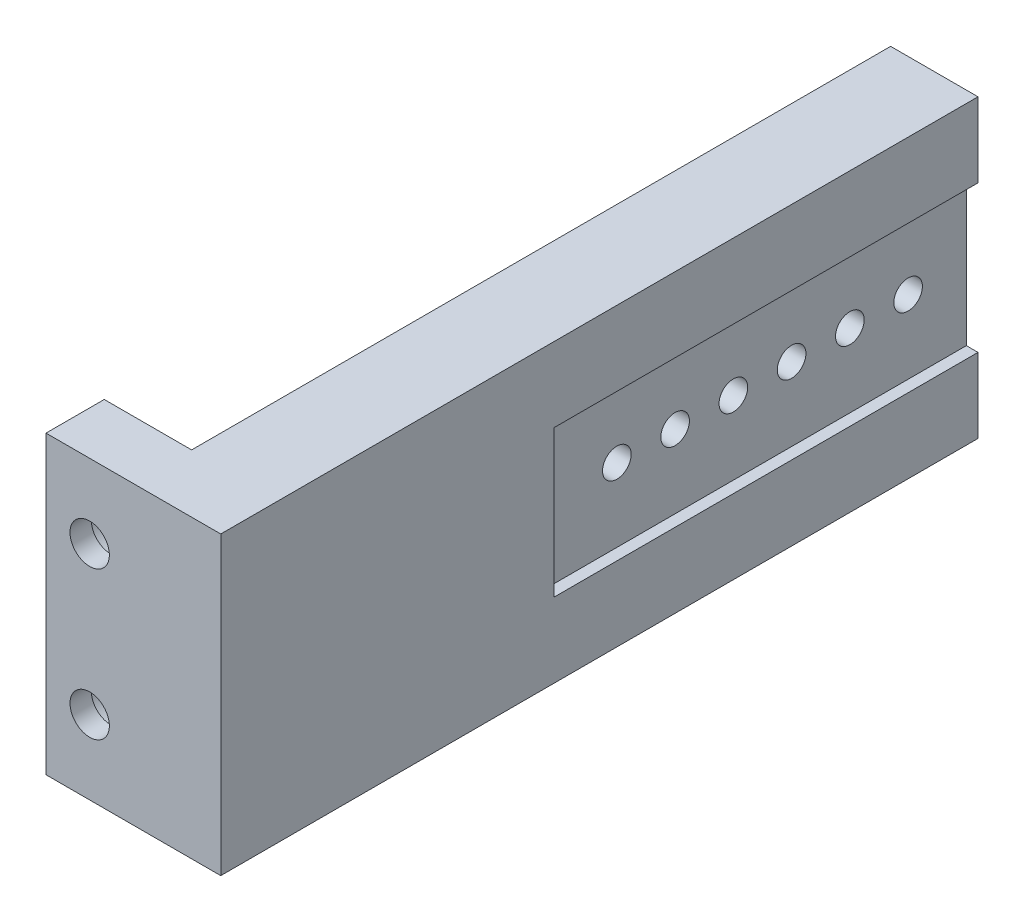
SolidWorks part; units mm, degrees
ref_plane "Front Plane" through (0, 0, 0) normal (0, 0, 1) x (1, 0, 0)
ref_plane "Top Plane" through (0, 0, 0) normal (0, 1, 0) x (1, 0, 0)
ref_plane "Right Plane" through (0, 0, 0) normal (1, 0, 0) x (0, 0, -1)
sketch "Sketch1" plane through (0, 0, 0) normal (0, 1, 0) x (1, 0, 0)
  line L1 (-82.9027, 73.5133) -> (-67.9027, 73.5133)
  line L2 (-82.9027, 73.5133) -> (-82.9027, -56.4867)
  line L3 (-82.9027, -56.4867) -> (-67.9027, -56.4867)
  line L4 (-67.9027, 73.5133) -> (-67.9027, -56.4867)
  line L5 (-82.9027, -56.4867) -> (-97.9027, -56.4867)
  line L7 (-82.9027, -46.4867) -> (-97.9027, -46.4867)
  line L8 (-97.9027, -56.4867) -> (-97.9027, -46.4867)
  dimension "D1" = 130
  dimension "D2" = 15
  dimension "D3" = 15
  dimension "D4" = 10
extrude "Boss-Extrude1" add sketch "Sketch1" along normal blind 50.8 contours L4 L1 L2 L3 | L8 L5 L2 L7
sketch "Sketch2" plane through (0, 0, 46.4867) normal (0, 0, -1) x (-1, 0, 0)
  line L0 (90.4027, 38.1) -> (90.4027, 12.7)
  line L1 (82.9027, 50.8) -> (97.9027, 50.8) construction
  line L3 (97.9027, 50.8) -> (97.9027, 0) construction
  dimension "D1" = 25.4
  dimension "D2" = 12.7
  dimension "D3" = 7.5
hole_wizard "CBORE for 1/4 Socket Head Cap Screw1" positions "Sketch3" profile "Sketch4" counterbore size "1/4" standard "ANSI Inch" end condition through all
sketch "Sketch3" plane through (0, 0, 46.4867) normal (0, 0, -1) x (-1, 0, 0)
  point P0 (90.4027, 12.7)
  point P3 (90.4027, 38.1)
sketch "Sketch4" plane through (-90.4027, 12.7, 46.4867) normal (1, 0, 0) x (0, 1, 0)
  line L0 (0, 0) -> (0, 10)
  line L1 (0, 10) -> (3.3782, 10)
  line L3 (3.3782, 10) -> (3.3782, 6.35)
  line L4 (3.3782, 6.35) -> (5.5562, 6.35)
  line L5 (5.5562, 6.35) -> (5.5562, 0)
  line L7 (5.5562, 0) -> (0, 0)
  line L11 (0, -6.35) -> (0, 107.95) construction
  dimension "Thru Hole Dia." = 6.7564
  dimension "Thru Hole Depth" = 10
  dimension "C'Bore Dia." = 11.1125
  dimension "C'Bore Depth" = 6.35
sketch "Sketch5" plane through (-67.9027, 0, 0) normal (1, 0, 0) x (0, 0, -1)
  line L0 (73.5133, 50.8) -> (-56.4867, 50.8) construction
  line L1 (63.5133, 25.4) -> (53.5133, 25.4)
  line L2 (63.5133, 25.4) -> (63.5133, 20)
  line L3 (63.5133, 20) -> (53.5133, 20)
  line L4 (53.5133, 25.4) -> (53.5133, 20)
  line L6 (73.5133, 50.8) -> (73.5133, 0) construction
  dimension "D1" = 25.4
  dimension "D3" = 10
  dimension "D4" = 10
hole_wizard "#8 Clearance Hole2" positions "Sketch8" profile "Sketch9" hole size "#8" standard "ANSI Inch" end condition through all
sketch "Sketch8" plane through (-67.9027, 0, 0) normal (1, 0, 0) x (0, 0, -1)
  point P0 (63.5133, 25.4)
  point P3 (53.5133, 25.4)
sketch "Sketch9" plane through (-67.9027, 25.4, -63.5133) normal (0, 1, 0) x (0, 0, -1)
  line L0 (0, 0) -> (0, 30)
  line L1 (0, 30) -> (2.4574, 30)
  line L2 (2.4574, 30) -> (2.4574, 0)
  line L5 (2.4574, 0) -> (0, 0)
  line L11 (0, -6.35) -> (0, 107.95) construction
  dimension "Thru Hole Dia." = 4.9149
  dimension "Thru Hole Depth" = 30
pattern_linear "LPattern1" count 3 spacing 20 along (0, 0, 1) of "#8 Clearance Hole2"
sketch "Sketch10" plane through (-67.9027, 0, 0) normal (1, 0, 0) x (0, 0, -1)
  line L0 (73.5133, 50.8) -> (73.5133, 0) construction
  line L1 (73.5133, 38) -> (0.7133, 38)
  line L2 (73.5133, 38) -> (73.5133, 12.8)
  line L3 (73.5133, 12.8) -> (0.7133, 12.8)
  line L4 (0.7133, 38) -> (0.7133, 12.8)
  line L5 (73.5133, 50.8) -> (-56.4867, 50.8) construction
  line L6 (73.5133, 0) -> (-56.4867, 0) construction
  circle A0 centre (13.5133, 25.4) radius 2.4574 construction
  dimension "D1" = 12.8
  dimension "D2" = 12.8
  dimension "D3" = 12.8
extrude "Cut-Extrude1" cut sketch "Sketch10" against normal blind 2
ref_plane "Plane1" through (-82.9027, 0, 46.4867) normal (0, -1, 0) x (-1, 0, 0)
sketch "Sketch13" plane through (0, 0, 46.4867) normal (0, 0, -1) x (-1, 0, 0)
  line L0 (82.9027, 50.8) -> (82.9027, 0) construction
  line L1 (82.9027, 22.7) -> (97.9027, 22.7)
  line L2 (82.9027, 22.7) -> (82.9027, 28.1)
  line L3 (82.9027, 28.1) -> (97.9027, 28.1)
  line L4 (97.9027, 22.7) -> (97.9027, 28.1)
  line L5 (97.9027, 50.8) -> (97.9027, 0) construction
  circle A0 centre (90.4027, 12.7) radius 3.3782 construction
  circle A1 centre (90.4027, 38.1) radius 3.3782 construction
  dimension "D1" = 10
  dimension "D2" = 10
extrude "Boss-Extrude2" add sketch "Sketch13" along normal blind 10
draft "Draft1" type of draft neutral plane draft angle 60 faces to draft 1 face at (-90.4027, 25.4, 36.4867) neutral plane through (-97.9027, 50.8, 0) neutral plane normal (-1, 0, 0) parameters "D1"=60
